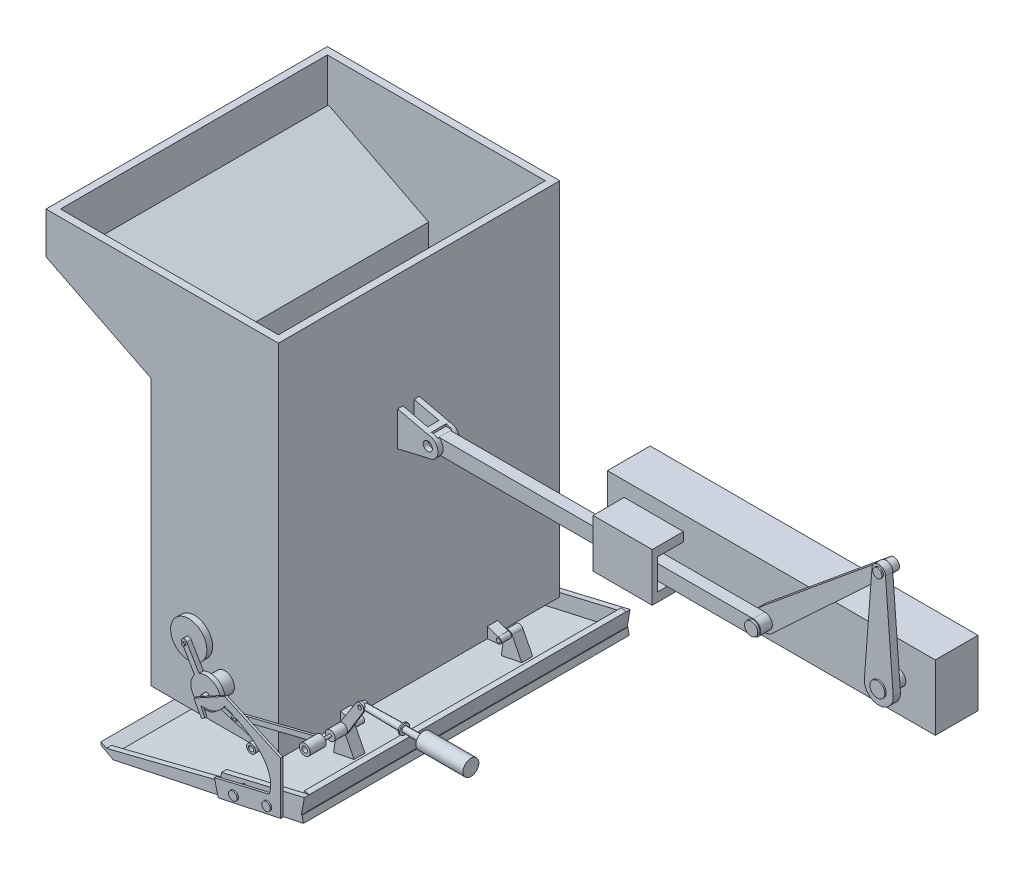
SolidWorks part; units mm, degrees
ref_plane "前视基准面" through (0, 0, 0) normal (0, 0, 1) x (1, 0, 0)
ref_plane "上视基准面" through (0, 0, 0) normal (0, 1, 0) x (1, 0, 0)
ref_plane "右视基准面" through (0, 0, 0) normal (1, 0, 0) x (0, 0, -1)
sketch "草图1" plane through (0, 0, 0) normal (0, 0, 1) x (1, 0, 0)
  line L1 (-43.2595, 0) -> (71.7598, 0)
  line L2 (-43.2595, 0) -> (-43.2595, -22.9274)
  line L3 (-43.2595, -22.9274) -> (71.7598, -22.9274)
  line L4 (71.7598, 0) -> (71.7598, -22.9274)
extrude "凸台-拉伸1" add sketch "草图1" along normal blind 14.986
sketch "草图2" plane through (0, 0, 14.986) normal (0, 0, 1) x (1, 0, 0)
  circle A0 centre (58.7859, -11.7435) radius 2.6281
extrude "凸台-拉伸2" add sketch "草图2" along normal blind 7.366
ref_plane "基准面1" through (0, 0, 21.844) normal (0, 0, 1) x (1, 0, 0)
sketch "草图3" plane through (0, 0, 21.844) normal (0, 0, 1) x (1, 0, 0)
  line L0 (53.7065, -11.7435) -> (56.4009, 23.5958)
  line L1 (63.8654, -11.7435) -> (61.171, 23.5958)
  arc A0 (53.7652, -10.9734) -> (63.8067, -10.9734) centre (58.7859, -11.7435) ccw
  arc A1 (61.171, 23.5958) -> (56.4009, 23.5958) centre (58.7859, 23.5958) ccw
extrude "凸台-拉伸3" add sketch "草图3" against normal blind 2.54 contours L1 A1 L0 A0
sketch "草图5" plane through (0, 0, 19.304) normal (0, 0, -1) x (-1, 0, 0)
  line L0 (-57.5365, 25.1089) -> (-13.9492, -10.8833)
  line L1 (-18.7214, -16.3288) -> (-60.122, 22.1586)
  arc A0 (-57.5365, 25.1089) -> (-60.122, 22.1586) centre (-58.7859, 23.5958) ccw
  arc A1 (-18.7214, -16.3288) -> (-13.9492, -10.8833) centre (-16.2554, -13.6761) ccw
extrude "凸台-拉伸4" add sketch "草图5" along normal blind 2.794
sketch "草图6" plane through (0, 0, 21.844) normal (0, 0, 1) x (1, 0, 0)
  circle A0 centre (58.7859, 23.5958) radius 1.6113
extrude "凸台-拉伸5" add sketch "草图6" along normal blind 0.508
sketch "草图7" plane through (0, 0, 19.304) normal (0, 0, 1) x (1, 0, 0)
  line L1 (16.2554, -11.0263) -> (-97.9751, -11.0263)
  line L3 (16.2554, -16.3259) -> (-97.9751, -16.3259)
  line L4 (-97.9751, -11.0263) -> (-97.9751, -16.3259)
  arc A0 (16.2554, -16.3259) -> (16.2554, -11.0263) centre (16.2554, -13.6761) ccw
extrude "凸台-拉伸6" add sketch "草图7" along normal blind 4.064 contours L1 L4 L3 A0
sketch "草图8" plane through (0, 0, 14.986) normal (0, 0, 1) x (1, 0, 0)
  line L0 (-97.9751, -13.6761) -> (22.4334, -13.6761) construction
  line L1 (-97.9751, -11.0263) -> (-97.9751, -16.3259) construction
  line L2 (-16.6339, -22.1522) -> (-16.6339, -19.0042)
  line L3 (-37.3784, -5.1999) -> (-16.6339, -5.1999)
  line L4 (-37.3784, -5.1999) -> (-37.3784, -8.3479)
  line L5 (-37.3784, -8.3479) -> (-16.6339, -8.3479)
  line L6 (-16.6339, -5.1999) -> (-16.6339, -8.3479)
  line L7 (-37.3784, -19.0042) -> (-16.6339, -19.0042)
  line L8 (-37.3784, -22.1522) -> (-37.3784, -19.0042)
  line L9 (-37.3784, -22.1522) -> (-16.6339, -22.1522)
extrude "凸台-拉伸7" add sketch "草图8" along normal blind 10.922
sketch "草图9" plane through (0, -8.3479, 0) normal (0, -1, 0) x (1, 0, 0)
  line L0 (-16.6339, 25.908) -> (-16.6339, 14.986) construction
  line L1 (-37.3784, 25.908) -> (-16.6339, 25.908)
  line L2 (-37.3784, 25.908) -> (-37.3784, 24.0036)
  line L3 (-37.3784, 24.0036) -> (-16.6339, 24.0036)
  line L4 (-16.6339, 25.908) -> (-16.6339, 24.0036)
extrude "凸台-拉伸8" add sketch "草图9" along normal blind 10.922
sketch "草图10" plane through (0, 0, 23.368) normal (0, 0, 1) x (1, 0, 0)
  circle A0 centre (16.3029, -13.6695) radius 2.2856
extrude "凸台-拉伸9" add sketch "草图10" along normal blind 0.762
sketch "草图11" plane through (0, 0, 0) normal (0, 0, -1) x (-1, 0, 0)
  circle A0 centre (-59.4451, -13.3537) radius 1.572
extrude "凸台-拉伸10" add sketch "草图11" along normal blind 3.302
sketch "草图12" plane through (0, 0, -3.302) normal (0, 0, -1) x (-1, 0, 0)
  line L1 (-67.8813, -5.7378) -> (-50.306, -5.7378)
  line L2 (-67.8813, -5.7378) -> (-67.8813, -22.4929)
  line L3 (-67.8813, -22.4929) -> (-50.306, -22.4929)
  line L4 (-50.306, -5.7378) -> (-50.306, -22.4929)
extrude "凸台-拉伸11" add sketch "草图12" along normal blind 13.462
sketch "草图13" plane through (0, 0, 16.51) normal (0, 0, -1) x (-1, 0, 0)
  circle A0 centre (-58.8502, 23.5206) radius 1.3313
  circle A1 centre (-58.8502, 23.5206) radius 1.0773
  dimension "D1" = 0.254
extrude "切除-拉伸1" cut sketch "草图13" against normal blind 0.762 contours A0 A1
ref_plane "基准面3" through (0, 0, 21.336) normal (0, 0, 1) x (1, 0, 0)
sketch "草图15" plane through (0, 0, 21.336) normal (0, 0, 1) x (1, 0, 0)
  line L0 (-106.6841, -7.8745) -> (-106.6841, -19.991)
  line L1 (-96.1372, -17.5247) -> (-106.6841, -19.991)
  line L3 (-96.1372, -10.3407) -> (-106.6841, -7.8745)
  arc A0 (-96.1372, -17.5247) -> (-96.1372, -10.3407) centre (-96.1372, -13.9327) ccw
  circle A1 centre (-96.1372, -13.9327) radius 1.6075
extrude "凸台-拉伸12" add sketch "草图15" along normal blind 3.81
sketch "草图16" plane through (0, 0, 21.336) normal (0, 0, 1) x (1, 0, 0)
  line L0 (-96.1372, -10.3407) -> (-106.6841, -7.8745) construction
  line L1 (-96.1372, -10.3407) -> (-106.6841, -7.8745)
  line L2 (-106.6841, -19.991) -> (-96.1372, -17.5247) construction
  line L3 (-106.6841, -7.8745) -> (-106.6841, -19.991) construction
  line L4 (-106.6841, -19.991) -> (-96.1372, -17.5247)
  line L5 (-106.6841, -7.8745) -> (-106.6841, -19.991)
  line L6 (-93.9749, -11.0644) -> (-96.1372, -11.0644)
  line L7 (-96.1372, -11.0644) -> (-96.1372, -10.3407)
  line L8 (-96.1372, -11.0644) -> (-97.9751, -11.0263)
  line L9 (-94.0264, -11.0263) -> (-97.9751, -11.0263) construction
  line L10 (-97.9751, -11.0263) -> (-97.9751, -16.4122)
  line L11 (-97.9751, -16.4122) -> (-93.5382, -16.4122)
  line L12 (-97.9751, -16.4122) -> (-97.9751, -17.9545)
  arc A0 (-96.1372, -17.5247) -> (-96.1372, -10.3407) centre (-96.1372, -13.9327) ccw construction
  arc A1 (-96.1372, -17.5247) -> (-96.1372, -10.3407) centre (-96.1372, -13.9327) ccw
extrude "切除-拉伸7" cut sketch "草图16" along normal blind 2.54 contours L6 A1 L7 | L4 A1 L11 L12
sketch "草图17" plane through (0, -16.3259, 0) normal (0, -1, 0) x (1, 0, 0)
  line L0 (-97.9751, 23.876) -> (-97.9751, 21.336) construction
  line L1 (-97.9751, 23.3009) -> (-109.7947, 23.3009)
  line L2 (-97.9751, 23.3009) -> (-97.9751, 20.2213)
  line L3 (-97.9751, 20.2213) -> (-109.7947, 20.2213)
  line L4 (-109.7947, 23.3009) -> (-109.7947, 20.2213)
extrude "切除-拉伸8" cut sketch "草图17" against normal mid plane 23.368
mirror "镜向2" about plane through (0, 0, 21.336) normal (0, 0, 1) of "凸台-拉伸12"
mirror "镜向3" about plane through (0, 0, 21.336) normal (0, 0, 1) of "切除-拉伸8", "切除-拉伸7"
sketch "草图18" plane through (-106.6841, 0, 0) normal (-1, 0, 0) x (0, 0, 1)
  line L1 (-31.7079, 33.0167) -> (66.9985, 33.0167)
  line L2 (-31.7079, 33.0167) -> (-31.7079, -93.4384)
  line L3 (-31.7079, -93.4384) -> (66.9985, -93.4384)
  line L4 (66.9985, 33.0167) -> (66.9985, -93.4384)
extrude "凸台-拉伸13" add sketch "草图18" along normal blind 81.534 separate body
shell "抽壳4" thickness 7.62
sketch "草图20" plane through (0, 0, 66.9985) normal (0, 0, 1) x (1, 0, 0)
  line L0 (-199.1591, 23.9686) -> (-151.3041, 0)
  line L1 (-151.3041, 0) -> (-151.3041, -110.7422)
  line L2 (-151.3041, -110.7422) -> (-215.8135, -106.7367)
  line L3 (-215.8135, -106.7367) -> (-199.1591, 23.9686)
extrude "切除-拉伸9" cut sketch "草图20" against normal blind 217.424
sketch "草图21" plane through (0, 0, -29.1679) normal (0, 0, 1) x (1, 0, 0)
  line L0 (-185.2719, 18.0198) -> (-150.1456, 0)
  line L1 (-150.1456, 0) -> (-150.1456, -93.4384)
  line L2 (-151.3041, -93.4384) -> (-106.6841, -93.4384) construction
  line L3 (-150.1456, -93.4384) -> (-151.3041, -93.4384)
  line L4 (-151.3041, -93.4384) -> (-151.3041, 0)
  line L5 (-151.3041, 0) -> (-185.2719, 17.0131)
  line L6 (-151.3041, 0) -> (-188.2181, 18.4887) construction
  line L7 (-185.2719, 17.0131) -> (-185.2719, 18.0198)
extrude "凸台-拉伸14" add sketch "草图21" along normal up to surface (93.6263 mm away) up to face at (-148.7354, -16.4245, 64.4585)
sketch "草图22" plane through (0, -90.8984, 0) normal (0, 1, 0) x (1, 0, 0)
  line L4 (-109.2241, 29.1679) -> (-150.1456, 29.1679)
  line L5 (-150.1456, 29.1679) -> (-150.1456, -64.4585)
  line L6 (-150.1456, -64.4585) -> (-109.2241, -64.4585)
  line L7 (-109.2241, -64.4585) -> (-109.2241, 29.1679)
  line L8 (-109.2241, 29.1679) -> (-150.1456, 29.1679)
  line L9 (-150.1456, 29.1679) -> (-150.1456, -64.4585)
  line L10 (-150.1456, -64.4585) -> (-109.2241, -64.4585)
  line L11 (-109.2241, -64.4585) -> (-109.2241, 29.1679)
  dimension "D1" = 0
extrude "切除-拉伸10" cut sketch "草图22" against normal blind 217.424
ref_plane "基准面4" through (0, 0, 17.6453) normal (0, 0, 1) x (1, 0, 0)
sketch "草图23" plane through (0, 0, 17.6453) normal (0, 0, 1) x (1, 0, 0)
  line L0 (-90.6, -98.4613) -> (-157.1509, -113.387)
  line L1 (-157.1509, -113.387) -> (-161.1896, -111.4554)
  line L2 (-161.1896, -111.4554) -> (-161.1896, -112.4212)
  line L3 (-161.1896, -112.4212) -> (-156.8448, -114.7517)
  line L4 (-156.8448, -114.7517) -> (-90.098, -100.6993)
  line L5 (-90.098, -100.6993) -> (-90.6, -98.4613)
extrude "凸台-拉伸15" add sketch "草图23" along normal mid plane 114.3 separate body
sketch "草图24" plane through (0, 0, 74.7953) normal (0, 0, 1) x (1, 0, 0)
  line L0 (-90.8306, -98.513) -> (-89.8019, -92.6914)
  line L1 (-90.6, -98.4613) -> (-157.1509, -113.387) construction
  line L2 (-89.8019, -92.6914) -> (-118.8261, -99.5527)
  line L3 (-118.8261, -99.5527) -> (-119.3354, -102.4348)
  line L4 (-119.3354, -102.4348) -> (-159.1703, -112.4212)
  line L5 (-157.1509, -113.387) -> (-161.1896, -111.4554) construction
  line L6 (-159.1703, -112.4212) -> (-157.1509, -113.387)
  line L7 (-157.1509, -113.387) -> (-90.8306, -98.513)
extrude "凸台-拉伸16" add sketch "草图24" against normal blind 1.778
sketch "草图25" plane through (-71.1983, 12.5819, 0) normal (0.9847, -0.174, 0) x (0, 0, -1)
  line L1 (-73.0173, -106.9045) -> (38.1396, -106.9045)
  line L2 (-73.0173, -106.9045) -> (-73.0173, -112.7252)
  line L3 (-73.0173, -112.7252) -> (38.1396, -112.7252)
  line L4 (38.1396, -106.9045) -> (38.1396, -112.7252)
extrude "凸台-拉伸18" add sketch "草图25" against normal blind 1.778
sketch "草图26" plane through (0, 0, 74.7953) normal (0, 0, 1) x (1, 0, 0)
  line L0 (-119.3354, -102.4348) -> (-91.3721, -96.0673) construction
  circle A0 centre (-110.5777, -100.4406) radius 1.4855
  circle A1 centre (-98.9084, -97.7834) radius 1.4855
extrude "凸台-拉伸19" add sketch "草图26" along normal blind 4.318
ref_plane "基准面5" through (0, 0, 77.8433) normal (0, 0, 1) x (1, 0, 0)
sketch "草图27" plane through (0, 0, 77.8433) normal (0, 0, 1) x (1, 0, 0)
  line L0 (-116.1623, -104.0715) -> (-94.2571, -99.3651)
  line L1 (-94.2571, -99.3651) -> (-94.2571, -81.0563)
  line L2 (-94.2571, -81.0563) -> (-113.9225, -72.1204)
  line L3 (-113.9225, -72.1204) -> (-124.7661, -78.0442)
  line L4 (-124.7661, -78.0442) -> (-122.0783, -82.8649)
  line L5 (-122.0783, -82.8649) -> (-120.8641, -82.1879)
  line L6 (-120.8641, -82.1879) -> (-122.3354, -79.0805)
  line L7 (-98.3276, -94.0488) -> (-117.5471, -98.5922)
  line L8 (-117.5471, -98.5922) -> (-116.1623, -104.0715)
  spline S0 degree 2 poles (-122.3354, -79.0805) (-116.918, -79.6407) (-113.9225, -75.0823) knots 0 0 0 1 1 1
  spline S1 degree 3 poles (-113.9225, -75.0823) (-106.7968, -77.6606) (-95.1642, -84.5323) (-98.3276, -94.0488) knots 0 0 0 0 1 1 1 1
extrude "凸台-拉伸20" add sketch "草图27" along normal blind 0.762
sketch "草图28" plane through (0, 0, 77.8433) normal (0, 0, -1) x (-1, 0, 0)
  circle A0 centre (103.9064, -82.6057) radius 1.554
  circle A1 centre (103.9064, -82.6057) radius 0.8768
extrude "凸台-拉伸21" add sketch "草图28" along normal mid plane 3.048 separate body
sketch "草图30" plane through (0, 0, 76.3193) normal (0, 0, -1) x (-1, 0, 0)
  line L0 (103.4544, -81.8122) -> (117.6456, -77.4431)
  line L1 (103.579, -83.2562) -> (118.0622, -78.7971)
  line L2 (125.198, -71.9242) -> (129.4731, -64.562)
  line L4 (131.1999, -65.5647) -> (126.7846, -73.1685)
  arc A0 (103.4544, -81.8122) -> (103.579, -83.2562) centre (103.4544, -82.5396) ccw
  arc A1 (125.198, -71.9242) -> (117.6456, -77.4431) centre (122.8173, -76.5933) ccw
  arc A2 (129.4731, -64.562) -> (131.1999, -65.5647) centre (130.3615, -65.0203) cw
  arc A3 (118.0622, -78.7971) -> (126.7846, -73.1685) centre (122.8173, -76.5933) ccw
extrude "凸台-拉伸22" add sketch "草图30" along normal blind 1.524
sketch "草图32" plane through (0, 0, 74.7953) normal (0, 0, -1) x (-1, 0, 0)
  circle A0 centre (130.3424, -64.936) radius 6.35
  dimension "D1" = 12.7
extrude "凸台-拉伸23" add sketch "草图32" along normal blind 2.032
sketch "草图33" plane through (0, 0, 76.3193) normal (0, 0, 1) x (1, 0, 0)
  circle A0 centre (-130.2837, -65.3914) radius 0.5183
extrude "凸台-拉伸24" add sketch "草图33" along normal blind 0.508
sketch "草图34" plane through (0, 0, 74.7953) normal (0, 0, -1) x (-1, 0, 0)
  line L4 (126.3763, -69.895) -> (125.198, -71.9242)
  line L5 (117.6456, -77.4431) -> (103.4544, -81.8122)
  line L6 (103.579, -83.2562) -> (118.0622, -78.7971)
  line L7 (126.7846, -73.1685) -> (128.1125, -70.8816)
  line L8 (126.3763, -69.895) -> (125.198, -71.9242)
  line L9 (117.6456, -77.4431) -> (103.4544, -81.8122)
  line L10 (103.579, -83.2562) -> (118.0622, -78.7971)
  line L11 (126.7846, -73.1685) -> (128.1125, -70.8816)
  circle A0 centre (122.8173, -76.5933) radius 3.4134
  arc A4 (126.3763, -69.895) -> (128.1125, -70.8816) centre (130.3424, -64.936) ccw
  arc A5 (125.198, -71.9242) -> (117.6456, -77.4431) centre (122.8173, -76.5933) ccw
  arc A6 (103.4544, -81.8122) -> (103.579, -83.2562) centre (103.4544, -82.5396) ccw
  arc A7 (118.0622, -78.7971) -> (126.7846, -73.1685) centre (122.8173, -76.5933) ccw
  arc A8 (126.3763, -69.895) -> (128.1125, -70.8816) centre (130.3424, -64.936) ccw
  arc A9 (125.198, -71.9242) -> (117.6456, -77.4431) centre (122.8173, -76.5933) ccw
  arc A10 (103.4544, -81.8122) -> (103.579, -83.2562) centre (103.4544, -82.5396) ccw
  arc A11 (118.0622, -78.7971) -> (126.7846, -73.1685) centre (122.8173, -76.5933) ccw
  dimension "D1" = 0
extrude "凸台-拉伸25" add sketch "草图34" along normal blind 5.08 contours A0
sketch "草图35" plane through (0, 0, 77.8433) normal (0, 0, -1) x (-1, 0, 0)
  circle A0 centre (122.4413, -77.1203) radius 0.821
extrude "凸台-拉伸26" add sketch "草图35" along normal blind 5.08
sketch "草图36" plane through (0, 0, 77.8433) normal (0, 0, -1) x (-1, 0, 0)
  circle A0 centre (110.753, -77.3984) radius 0.8715
  circle A1 centre (110.753, -77.3984) radius 0.4294
extrude "凸台-拉伸27" add sketch "草图36" against normal mid plane 1.27 separate body
sketch "草图37" plane through (0, 0, 77.2083) normal (0, 0, -1) x (-1, 0, 0)
  line L0 (110.753, -76.5269) -> (81.8987, -69.2974)
  line L2 (81.4466, -70.9542) -> (110.5411, -78.2438)
  arc A0 (110.5411, -78.2438) -> (110.753, -76.5269) centre (110.753, -77.3984) ccw
  arc A1 (81.8987, -69.2974) -> (81.4814, -70.9629) centre (81.6726, -70.1258) ccw
  circle M4 centre (110.753, -77.3984) radius 0.8715
extrude "凸台-拉伸28" add sketch "草图37" along normal blind 0.762 separate body contours L0 A1 L2 M4
sketch "草图38" plane through (0, 0, 77.2083) normal (0, 0, 1) x (1, 0, 0)
  circle A0 centre (-81.632, -70.0412) radius 1.905
  circle A1 centre (-81.632, -70.0412) radius 0.9525
  dimension "D1" = 3.81
extrude "凸台-拉伸29" add sketch "草图38" along normal blind 5.588
sketch "草图39" plane through (0, 0, 76.4463) normal (0, 0, -1) x (-1, 0, 0)
  circle A0 centre (81.5826, -70.1853) radius 0.4698
extrude "凸台-拉伸30" add sketch "草图39" along normal blind 2.54
sketch "草图40" plane through (0, 0, 73.9063) normal (0, 0, -1) x (-1, 0, 0)
  circle A0 centre (81.5826, -70.1853) radius 1.6938
extrude "凸台-拉伸31" add sketch "草图40" along normal blind 4.318
sketch "草图41" plane through (0, 0, 69.5883) normal (0, 0, -1) x (-1, 0, 0)
  line L0 (82.4832, -68.7507) -> (76.8125, -59.9977)
  line L1 (80.136, -71.0664) -> (74.3612, -61.5859)
  arc A0 (76.8125, -59.9977) -> (74.3612, -61.5859) centre (75.5868, -60.7918) ccw
  circle A1 centre (81.5826, -70.1853) radius 1.6938
  arc A2 (80.136, -71.0664) -> (82.4832, -68.7507) centre (81.5826, -70.1853) ccw
  circle A3 centre (75.5868, -60.7918) radius 0.6688
  dimension "D1" = 0
extrude "凸台-拉伸32" add sketch "草图41" along normal blind 0.762
sketch "草图42" plane through (0, 0, 68.8263) normal (0, 0, -1) x (-1, 0, 0)
  circle A0 centre (75.5868, -60.7918) radius 1.0872
extrude "凸台-拉伸33" add sketch "草图42" along normal blind 1.27
ref_plane "基准面8" through (0, 0, 68.3183) normal (0, 0, -1) x (-1, 0, 0)
sketch "草图43" plane through (0, 0, 68.3183) normal (0, 0, -1) x (-1, 0, 0)
  line L0 (75.5868, -60.7918) -> (61.5482, -60.7918)
  line L2 (61.5482, -59.647) -> (75.5868, -59.8538)
  line L3 (75.5868, -59.8538) -> (75.5868, -60.7918)
  line L4 (61.5482, -59.647) -> (61.5482, -59.0126)
  line L5 (61.5482, -59.0126) -> (61.0711, -59.0126)
  line L6 (61.0711, -59.0126) -> (61.0711, -59.8538)
  line L8 (61.0711, -60.7918) -> (61.5482, -60.7918)
  line L9 (61.0711, -59.8538) -> (55.1418, -59.7664)
  line L11 (55.1418, -60.7918) -> (61.0711, -60.7918)
  line L12 (55.1418, -59.7664) -> (55.1418, -59.0126)
  line L13 (55.1418, -59.0126) -> (54.3827, -59.0126)
  line L15 (54.3827, -60.7918) -> (55.1418, -60.7918)
  line L16 (54.3827, -59.0126) -> (54.3827, -58.0055)
  line L17 (54.3827, -58.0055) -> (37.8264, -58.0055)
  line L18 (37.8264, -58.0055) -> (37.8264, -60.7918)
  line L19 (37.8264, -60.7918) -> (54.3827, -60.7918)
revolve "旋转1" add sketch "草图43" angle 360 about L19
mirror "镜向5" about plane through (0, 0, 17.6453) normal (0, 0, 1) of "凸台-拉伸16"
ref_plane "基准面9" through (0, 0, 41.5985) normal (0, 0, 1) x (1, 0, 0)
sketch "草图46" plane through (0, 0, 41.5985) normal (0, 0, 1) x (1, 0, 0)
  line L0 (-106.6841, -89.6659) -> (-102.8617, -90.9372)
  line L1 (-106.6841, -93.4384) -> (-106.6841, 33.0167) construction
  line L3 (-102.8617, -93.0824) -> (-106.6841, -93.4384)
  line L4 (-106.6841, -93.4384) -> (-106.6841, -89.6659)
  arc A0 (-102.8617, -93.0824) -> (-102.8617, -90.9372) centre (-102.8617, -92.0098) ccw
  circle A1 centre (-102.8617, -92.0098) radius 0.6976
extrude "凸台-拉伸34" add sketch "草图46" along normal blind 3.556
sketch "草图47" plane through (0, 0, 45.1545) normal (0, 0, 1) x (1, 0, 0)
  line L0 (-104.263, -91.8182) -> (-105.3338, -99.6484)
  line L1 (-105.3338, -99.6484) -> (-98.1625, -98.2137)
  line L2 (-98.1625, -98.2137) -> (-101.5431, -91.4984)
  arc A0 (-101.5431, -91.4984) -> (-104.263, -91.8182) centre (-102.8617, -92.0098) ccw
extrude "凸台-拉伸35" add sketch "草图47" along normal blind 3.81
mirror "镜向6" about plane through (0, 0, 17.6453) normal (0, 0, 1) of "凸台-拉伸35", "凸台-拉伸34"
sketch "草图48" plane through (67.8813, 0, 0) normal (1, 0, 0) x (0, 0, -1)
  line L1 (3.0655, -2.2565) -> (19.1911, -2.2565)
  line L2 (3.0655, -2.2565) -> (3.0655, -26.0173)
  line L3 (3.0655, -26.0173) -> (19.1911, -26.0173)
  line L4 (19.1911, -2.2565) -> (19.1911, -26.0173)
extrude "切除-拉伸11" cut sketch "草图48" against normal blind 23.114
